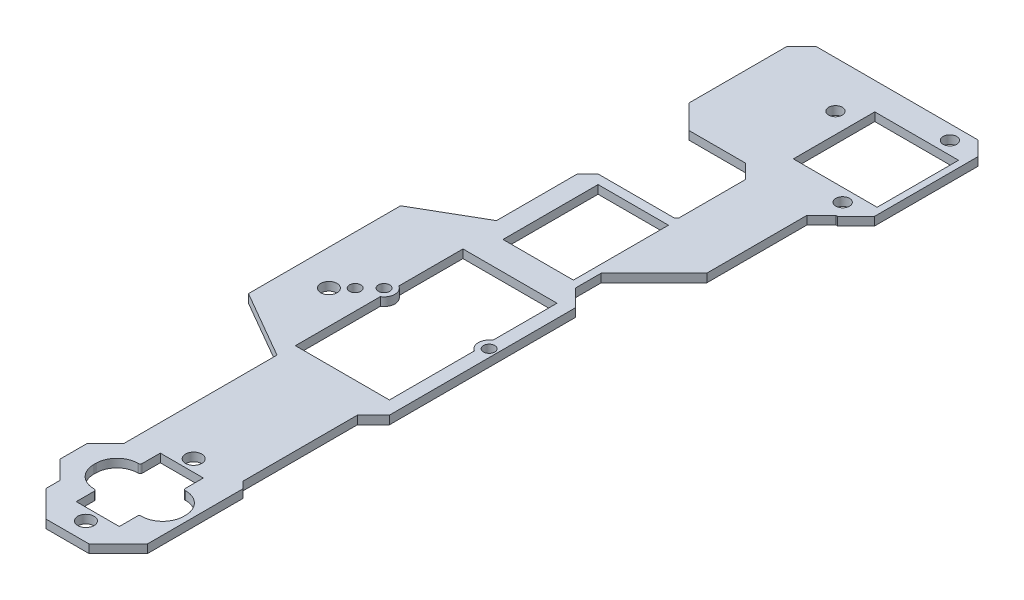
SolidWorks part; units mm, degrees
other "细节项目1" parameters "D6"=0, "D7"=43.265, "D8"=21.3195, "D9"=3.1, "D42"=2.165, "D1"=165.3052, "D2"=19.5925, "D3"=0.6425, "D4"=2.44, "D5"=17.2133, "D10"=7.7328, "D11"=1.0157, "D12"=7.6288, "D13"=2.2322, "D14"=28, "D15"=2.9581, "D16"=9.0669, "D17"=13.2064, "D18"=25.6687, "D19"=10.6252, "D20"=8.1415, "D21"=2.5001, "D22"=18.1, "D23"=31.9, "D24"=8.325, "D25"=16.4296, "D26"=39.8645, "D27"=14.2738, "D28"=3.5, "D29"=1.9207, "D30"=2.6491, "D31"=2.8766, "D32"=165.3052, "D33"=2.9084, "D34"=2.742, "D35"=4.9181, "D36"=3.9323, "D37"=15.95, "D38"=0.6899, "D39"=4.8396, "D40"=4.8539, "D41"=1.181, "D43"=5.1085, "D44"=5.1085, "D45"=13.8946, "D46"=1.2516
other "细节项目2"
other "DetailItem1" parameters "D1"=37.7393, "D2"=41.5714, "D3"=31.9, "D4"=17.9, "D5"=2.3612, "D6"=17.9
other "DetailItem2"
other "DetailItem3"
other "DetailItem4"
other "标注1"
sketch "草图2" plane through (-130.8299, 1.6, -83.1559) normal (0, 1, 0) x (1, 0, 0)
ref_plane "前视基准面" through (0, 0, 0) normal (0, 0, 1) x (1, 0, 0)
ref_plane "上视基准面" through (0, 0, 0) normal (0, 1, 0) x (1, 0, 0)
ref_plane "右视基准面" through (0, 0, 0) normal (1, 0, 0) x (0, 0, -1)
sketch "主结构参考-草图" plane through (0, 0, 0) normal (0, 1, 0) x (1, 0, 0)
  line L0 (0, 0) -> (0, -182.3314) construction
  line L1 (-33.5123, 83.1559) -> (-28.0234, 81.2061)
  line L2 (-19, -38) -> (-25.5, -38)
  line L3 (-25.5, -38) -> (-25.5, -41.5)
  line L4 (-25.5, -41.5) -> (-19, -41.5)
  line L5 (-19, -41.5) -> (-19, -38)
  line L6 (-35.683, -46.5466) -> (-25.6169, -51.6755)
  line L7 (-22.9814, -57.0983) -> (-24.5, -64.7956)
  line L8 (-24.5, -64.7956) -> (-24.5, -72.3717)
  line L9 (-24.5, -72.3717) -> (-22.5, -72.3717)
  line L10 (-22.5, -72.3717) -> (-22.5, -79.9478)
  line L11 (-22.5, -79.9478) -> (-24.1099, -79.9478)
  line L12 (-24.8532, -80.1135) -> (-37.6736, -86.1277)
  line L13 (-38.6804, -87.712) -> (-38.6804, -93.35)
  line L14 (-36.9304, -95.1) -> (-27.7511, -95.1)
  line L15 (-26.0011, -96.85) -> (-26.0011, -102.35)
  line L16 (-26.0011, -102.35) -> (-22.5, -102.35)
  line L17 (-22.5, -102.35) -> (-22.5, -110.35)
  line L18 (-22.5, -110.35) -> (-26.0011, -110.35)
  line L19 (-26.0011, -110.35) -> (-26.0011, -117.6)
  line L20 (-26.0011, -117.6) -> (-24.5011, -117.6)
  line L21 (-24.5011, -117.6) -> (-24.5011, -130.1)
  line L22 (-24.5011, -130.1) -> (-26.0011, -130.1)
  line L23 (0.0009, -58.5) -> (-4.1009, -58.5)
  line L25 (-4.1009, -58.5) -> (-4.1009, -61.9511)
  line L26 (-4.4509, -62.3011) -> (-4.5484, -62.3011)
  line L27 (-8.5484, -66.3011) -> (-8.5484, -66.6961)
  line L28 (-8.5484, -66.4986) -> (0, -66.4986) construction
  line L29 (-4.4509, -70.6961) -> (-4.5484, -70.6961)
  line L30 (-4.1009, -74.4972) -> (-4.1009, -71.0461)
  line L31 (0.0009, -74.4972) -> (-4.1009, -74.4972)
  line L32 (-0.0009, -58.5) -> (4.1009, -58.5)
  line L33 (4.1009, -58.5) -> (4.1009, -61.9511)
  line L34 (4.4509, -62.3011) -> (4.5484, -62.3011)
  line L35 (8.5484, -66.3011) -> (8.5484, -66.6961)
  line L36 (4.4509, -70.6961) -> (4.5484, -70.6961)
  line L37 (4.1009, -74.4972) -> (4.1009, -71.0461)
  line L38 (-0.0009, -74.4972) -> (4.1009, -74.4972)
  line L39 (25.5, -41.5) -> (19, -41.5)
  line L40 (25.5, -38) -> (25.5, -41.5)
  line L41 (19, -38) -> (25.5, -38)
  line L42 (19, -41.5) -> (19, -38)
  line L43 (24.5011, -130.1) -> (26.0011, -130.1)
  line L44 (24.5011, -117.6) -> (24.5011, -130.1)
  line L45 (26.0011, -117.6) -> (24.5011, -117.6)
  line L46 (26.0011, -110.35) -> (26.0011, -117.6)
  line L47 (22.5, -110.35) -> (26.0011, -110.35)
  line L48 (22.5, -102.35) -> (22.5, -110.35)
  line L49 (26.0011, -102.35) -> (22.5, -102.35)
  line L50 (26.0011, -96.85) -> (26.0011, -102.35)
  line L51 (36.9304, -95.1) -> (27.7511, -95.1)
  line L52 (38.6804, -87.712) -> (38.6804, -93.35)
  line L53 (24.8532, -80.1135) -> (37.6736, -86.1277)
  line L54 (22.5, -79.9478) -> (24.1099, -79.9478)
  line L55 (22.5, -72.3717) -> (22.5, -79.9478)
  line L56 (24.5, -72.3717) -> (22.5, -72.3717)
  line L57 (24.5, -64.7956) -> (24.5, -72.3717)
  line L58 (22.9814, -57.0983) -> (24.5, -64.7956)
  line L59 (35.683, -46.5466) -> (25.6169, -51.6755)
  line L60 (0, 0) -> (-130.8299, 0) construction
  line L61 (10.5, -81) -> (-10.5, -81)
  line L63 (-11.8487, -82.2911) -> (-13.5761, -121.8546)
  line L64 (-13.5761, -121.8546) -> (-13.5793, -125.7684)
  line L65 (-12.5918, -128.1539) -> (-7.25, -133.5)
  line L66 (-7.25, -133.5) -> (7.25, -133.5)
  line L68 (12.5918, -128.1539) -> (7.25, -133.5)
  line L69 (13.5761, -121.8546) -> (13.5793, -125.7684)
  line L70 (11.8487, -82.2911) -> (13.5761, -121.8546)
  line L85 (33.5123, 83.1559) -> (28.0234, 81.2061)
  line L99 (30.2498, 22.1218) -> (29.86, 20.4977)
  line L100 (31.0056, 27.0574) -> (30.2498, 22.1218)
  line L101 (27.1476, 31.0325) -> (20.9845, 30.1828)
  line L102 (29.86, -20.4977) -> (30.2498, -22.1218)
  line L103 (30.2498, -22.1218) -> (31.0056, -27.0574)
  line L104 (27.1476, -31.0325) -> (20.9845, -30.1828)
  line L105 (26.3691, 78.6288) -> (27.5605, 59.15)
  line L106 (-27.1476, -31.0325) -> (-20.9845, -30.1828)
  line L107 (-30.2498, -22.1218) -> (-31.0056, -27.0574)
  line L108 (-29.86, -20.4977) -> (-30.2498, -22.1218)
  line L109 (-30.2498, 22.1218) -> (-29.86, 20.4977)
  line L110 (-31.0056, 27.0574) -> (-30.2498, 22.1218)
  line L111 (-27.1476, 31.0325) -> (-20.9845, 30.1828)
  line L112 (25.5, 41.5) -> (19, 41.5)
  line L113 (19, 41.5) -> (19, 38)
  line L114 (19, 38) -> (25.5, 38)
  line L115 (25.5, 38) -> (25.5, 41.5)
  line L116 (5.75, 41.5) -> (-5.75, 41.5)
  line L117 (-5.75, 41.5) -> (-5.75, 38)
  line L118 (-5.75, 38) -> (5.75, 38)
  line L119 (5.75, 38) -> (5.75, 41.5)
  line L120 (23.6, 65.75) -> (7.65, 65.75)
  line L121 (7.65, 65.75) -> (7.65, 50.25)
  line L122 (7.65, 50.25) -> (23.6, 50.25)
  line L123 (23.6, 50.25) -> (23.6, 65.75)
  line L124 (-5.75, 38) -> (-5.75, 41.5)
  line L125 (5.75, 41.5) -> (5.75, 38)
  line L126 (-25.5, 38) -> (-25.5, 41.5)
  line L127 (-19, 38) -> (-25.5, 38)
  line L128 (-19, 41.5) -> (-19, 38)
  line L129 (-25.5, 41.5) -> (-19, 41.5)
  line L133 (27.8403, 57.7795) -> (29.754, 52.4001)
  line L134 (32.155, 49.6414) -> (40.1936, 45.4544)
  line L135 (-32.155, 49.6414) -> (-40.1936, 45.4544)
  line L136 (-27.8403, 57.7795) -> (-29.754, 52.4001)
  line L137 (-26.3691, 78.6288) -> (-27.5605, 59.15)
  arc A0 (-28.0234, 81.2061) -> (-26.3649, 78.6977) centre (-28.8602, 78.8503) cw
  arc A3 (28.0234, 81.2061) -> (26.3649, 78.6977) centre (28.8602, 78.8503) ccw
  circle A6 centre (-32, -42) radius 1.55
  circle A7 centre (-17.5, -47.5) radius 1.55
  arc A10 (-35.683, -46.5466) -> (-57.02, -48.2258) centre (-44.9813, -64.7956) ccw
  arc A12 (-22.9814, -57.0983) -> (-25.6169, -51.6755) centre (-27.8869, -56.1305) ccw
  arc A14 (-24.8532, -80.1135) -> (-24.1099, -79.9478) centre (-24.1099, -81.6978) cw
  arc A15 (-37.6736, -86.1277) -> (-38.6804, -87.712) centre (-36.9304, -87.712) ccw
  arc A16 (-38.6804, -93.35) -> (-36.9304, -95.1) centre (-36.9304, -93.35) ccw
  arc A17 (-27.7511, -95.1) -> (-26.0011, -96.85) centre (-27.7511, -96.85) cw
  circle A18 centre (0, -56.25) radius 1.55
  circle A19 centre (0, -76.75) radius 1.55
  circle A20 centre (-16.866, -65.108) radius 1.55
  arc A24 (-4.1009, -61.9511) -> (-4.4509, -62.3011) centre (-4.4509, -61.9511) cw
  arc A25 (-4.5484, -62.3011) -> (-8.5484, -66.3011) centre (-4.5484, -66.3011) ccw
  arc A26 (-4.5484, -70.6961) -> (-8.5484, -66.6961) centre (-4.5484, -66.6961) cw
  arc A27 (-4.1009, -71.0461) -> (-4.4509, -70.6961) centre (-4.4509, -71.0461) ccw
  arc A28 (4.1009, -61.9511) -> (4.4509, -62.3011) centre (4.4509, -61.9511) ccw
  arc A29 (4.5484, -62.3011) -> (8.5484, -66.3011) centre (4.5484, -66.3011) cw
  arc A30 (4.5484, -70.6961) -> (8.5484, -66.6961) centre (4.5484, -66.6961) ccw
  arc A31 (4.1009, -71.0461) -> (4.4509, -70.6961) centre (4.4509, -71.0461) cw
  circle A32 centre (32, -42) radius 1.55
  circle A33 centre (17.5, -47.5) radius 1.55
  arc A34 (27.7511, -95.1) -> (26.0011, -96.85) centre (27.7511, -96.85) ccw
  arc A35 (38.6804, -93.35) -> (36.9304, -95.1) centre (36.9304, -93.35) cw
  arc A36 (37.6736, -86.1277) -> (38.6804, -87.712) centre (36.9304, -87.712) cw
  arc A37 (24.8532, -80.1135) -> (24.1099, -79.9478) centre (24.1099, -81.6978) ccw
  arc A38 (22.9814, -57.0983) -> (25.6169, -51.6755) centre (27.8869, -56.1305) cw
  arc A39 (35.683, -46.5466) -> (57.02, -48.2258) centre (44.9813, -64.7956) cw
  circle A41 centre (16.866, -65.108) radius 1.55
  circle A42 centre (-34.5, -90.85) radius 1.55
  circle A43 centre (-16.9, -98.4) radius 1.55
  arc A44 (-10.5, -81) -> (-11.8487, -82.2911) centre (-10.5, -82.35) ccw
  arc A45 (-13.5793, -125.7684) -> (-12.5918, -128.1539) centre (-10.211, -125.7712) ccw
  circle A48 centre (-14.6, -133.5) radius 1.55
  circle A49 centre (-22.35, -133.5) radius 1.55
  arc A52 (13.5793, -125.7684) -> (12.5918, -128.1539) centre (10.211, -125.7712) cw
  arc A53 (10.5, -81) -> (11.8487, -82.2911) centre (10.5, -82.35) cw
  arc A63 (29.86, 20.4977) -> (29.86, -20.4977) centre (91.8849, 0) ccw
  arc A64 (31.0056, 27.0574) -> (27.1476, 31.0325) centre (28, 28) ccw
  arc A65 (20.9845, 30.1828) -> (18.059, 29.3089) centre (22.3504, 20.2765) ccw
  arc A66 (18.059, 29.3089) -> (-18.059, 29.3089) centre (0, 67.3193) cw
  arc A67 (31.0056, -27.0574) -> (27.1476, -31.0325) centre (28, -28) cw
  arc A68 (20.9845, -30.1828) -> (18.059, -29.3089) centre (22.3504, -20.2765) cw
  arc A69 (18.059, -29.3089) -> (-18.059, -29.3089) centre (0, -67.3193) ccw
  arc A70 (-20.9845, -30.1828) -> (-18.059, -29.3089) centre (-22.3504, -20.2765) ccw
  arc A71 (-31.0056, -27.0574) -> (-27.1476, -31.0325) centre (-28, -28) ccw
  arc A72 (-29.86, 20.4977) -> (-29.86, -20.4977) centre (-91.8849, 0) cw
  arc A73 (-31.0056, 27.0574) -> (-27.1476, 31.0325) centre (-28, 28) cw
  arc A74 (-20.9845, 30.1828) -> (-18.059, 29.3089) centre (-22.3504, 20.2765) cw
  circle A75 centre (36, 43) radius 1.55
  circle A76 centre (29.25, 40.5) radius 1.55
  circle A77 centre (19.5, 47.8) radius 1.3
  circle A78 centre (19.5, 68.2) radius 1.3
  circle A79 centre (3.8, 62.12) radius 1.3
  circle A80 centre (3.8, 74.15) radius 1.3
  circle A81 centre (-20.5, 74.15) radius 1.3
  circle A82 centre (-20.5, 62.12) radius 1.3
  circle A83 centre (-15, 53.5) radius 1.55
  circle A84 centre (-29.25, 40.5) radius 1.55
  circle A85 centre (-36, 43) radius 1.55
  arc A86 (27.5605, 59.15) -> (27.8403, 57.7795) centre (32.5512, 59.4553) ccw
  arc A87 (29.754, 52.4001) -> (32.155, 49.6414) centre (34.4648, 54.0759) ccw
  arc A88 (-29.754, 52.4001) -> (-32.155, 49.6414) centre (-34.4648, 54.0759) cw
  arc A89 (-27.5605, 59.15) -> (-27.8403, 57.7795) centre (-32.5512, 59.4553) cw
  point P249 (0, -133.5)
  point P250 (0, -81)
sketch "主结构参考2-草图" plane through (0, 0, 0) normal (0, 1, 0) x (1, 0, 0)
  line L0 (0, 0) -> (164.4446, 0) construction
  line L1 (56.8328, -48.3989) -> (84.4776, -68.4839)
  line L2 (0, -78.6558) -> (0, 78.6558) construction
  line L3 (-56.8328, -48.3989) -> (-84.4776, -68.4839)
  line L4 (0.25, -4.6996) -> (11.5388, -19.5881)
  line L5 (11.5388, -19.5881) -> (13.7761, -22.9243)
  line L6 (4.3699, 0) -> (22.5859, -13.8118)
  line L8 (4.3699, 0) -> (22.5859, 13.8118)
  line L9 (-11.5388, -19.5881) -> (-13.7761, -22.9243)
  line L10 (-0.25, -4.6996) -> (-11.5388, -19.5881)
  line L11 (56.8328, -48.3989) -> (84.4776, -68.4839)
  line L12 (-0.25, -29.9331) -> (0.25, -29.9331)
  line L13 (-56.8328, -48.3989) -> (-84.4776, -68.4839)
  line L15 (-4.3699, 0) -> (-22.5859, 13.8118)
  line L17 (-0.25, -4.6996) -> (0.25, -4.6996)
  line L18 (-0.25, -21.5644) -> (0.25, -21.5644)
  line L23 (30.5, 3.25) -> (30.5, -3.25)
  line L28 (34, 3.25) -> (30.5, 3.25)
  line L29 (-30.5, -3.25) -> (-34, -3.25)
  line L30 (-34, -3.25) -> (-34, 3.25)
  line L31 (-34, 3.25) -> (-30.5, 3.25)
  line L32 (-30.5, 3.25) -> (-30.5, -3.25)
  line L33 (-4.3699, 0) -> (-22.5859, -13.8118)
  line L34 (34, -3.25) -> (34, 3.25)
  line L35 (30.5, -3.25) -> (34, -3.25)
  line L36 (-0.25, 29.9331) -> (0.25, 29.9331)
  line L37 (-11.5388, 19.5881) -> (-13.7761, 22.9243)
  line L38 (-0.25, 4.6996) -> (-11.5388, 19.5881)
  line L39 (-0.25, 4.6996) -> (0.25, 4.6996)
  line L40 (0.25, 4.6996) -> (11.5388, 19.5881)
  line L41 (11.5388, 19.5881) -> (13.7761, 22.9243)
  line L42 (-0.25, 21.5644) -> (0.25, 21.5644)
  arc A0 (0.25, -29.9331) -> (56.8328, -48.3989) centre (0, -126.6225) cw
  circle A1 centre (-60.2246, -43.7557) radius 1.55
  arc A2 (-0.25, -29.9331) -> (-56.8328, -48.3989) centre (0, -126.6225) ccw
  arc A3 (0.25, -21.5644) -> (13.7761, -22.9243) centre (0, -91.9966) cw
  circle A4 centre (-44.0442, -32) radius 1.55
  circle A8 centre (-12.75, -12.75) radius 1.075
  circle A9 centre (-10, -10) radius 1.075
  circle A10 centre (-15.25, -15.25) radius 1.55
  arc A13 (-0.25, -21.5644) -> (-13.7761, -22.9243) centre (0, -91.9966) ccw
  arc A14 (0.25, -29.9331) -> (56.8328, -48.3989) centre (0, -126.6225) cw
  arc A15 (-0.25, -29.9331) -> (-56.8328, -48.3989) centre (0, -126.6225) ccw
  circle A16 centre (15.25, -15.25) radius 1.55
  circle A17 centre (10, -10) radius 1.075
  circle A18 centre (12.75, -12.75) radius 1.075
  circle A19 centre (44.0442, -32) radius 1.55
  circle A20 centre (60.2246, -43.7557) radius 1.55
  arc A24 (-28.8648, 17.1963) -> (-22.5859, 13.8118) centre (-41.8919, -14.4887) cw
  arc A25 (-28.8648, -17.1963) -> (-28.8648, 17.1963) centre (-91.8849, 0) ccw
  arc A26 (-22.5859, -13.8118) -> (-28.8648, -17.1963) centre (-41.8919, 14.4887) cw
  arc A27 (22.5859, -13.8118) -> (28.8648, -17.1963) centre (41.8919, 14.4887) ccw
  arc A28 (28.8648, -17.1963) -> (28.8648, 17.1963) centre (91.8849, 0) cw
  arc A29 (28.8648, 17.1963) -> (22.5859, 13.8118) centre (41.8919, -14.4887) ccw
  arc A30 (0.25, 29.9331) -> (56.8328, 48.3989) centre (0, 126.6225) ccw
  arc A31 (-0.25, 29.9331) -> (-56.8328, 48.3989) centre (0, 126.6225) cw
  arc A32 (-0.25, 21.5644) -> (-13.7761, 22.9243) centre (0, 91.9966) cw
  arc A33 (0.25, 21.5644) -> (13.7761, 22.9243) centre (0, 91.9966) ccw
  circle A34 centre (15.25, 15.25) radius 1.55
  circle A35 centre (12.75, 12.75) radius 1.075
  circle A36 centre (10, 10) radius 1.075
  circle A37 centre (-10, 10) radius 1.075
  circle A38 centre (-12.75, 12.75) radius 1.075
  circle A39 centre (-15.25, 15.25) radius 1.55
sketch "飞塔保护壳-参考-草图" plane through (0, 0, 0) normal (0, 1, 0) x (1, 0, 0)
  line L1 (-61.3007, 0) -> (77.257, 0) construction
  line L8 (-30.5, 3.25) -> (-34, 3.25)
  line L9 (-34, 3.25) -> (-34, -3.25)
  line L31 (-34, -3.25) -> (-30.5, -3.25)
  line L33 (-25.5, 38) -> (-25.5, 41.5)
  line L56 (-25.5, 41.5) -> (-19, 41.5)
  line L57 (-19, 41.5) -> (-19, 38)
  line L58 (-25.5, -38) -> (-25.5, -41.5)
  line L59 (-25.5, -41.5) -> (-19, -41.5)
  line L60 (-19, -41.5) -> (-19, -38)
  line L61 (19, -41.5) -> (19, -38)
  line L62 (25.5, -41.5) -> (19, -41.5)
  line L63 (25.5, -38) -> (25.5, -41.5)
  line L64 (19, 41.5) -> (19, 38)
  line L65 (25.5, 41.5) -> (19, 41.5)
  line L66 (25.5, 38) -> (25.5, 41.5)
  line L67 (34, -3.25) -> (30.5, -3.25)
  line L68 (34, 3.25) -> (34, -3.25)
  line L69 (30.5, 3.25) -> (34, 3.25)
  line L70 (-5.75, 38) -> (-5.75, 41.5)
  line L71 (-5.75, 41.5) -> (5.75, 41.5)
  line L72 (5.75, 41.5) -> (5.75, 38)
  line L73 (-5.75, 38) -> (-7.25, 36.5)
  line L75 (0, 68.5797) -> (0, -68.5797) construction
  line L78 (5.75, 38) -> (7.25, 36.5)
  line L83 (5.75, 38) -> (5.75, 32.8597)
  line L84 (19, 38) -> (19, 34.26)
  line L85 (-11.4662, -31.3366) -> (-10.3252, -32.103)
  line L86 (-10.3252, -32.103) -> (-10, -33.9347)
  line L87 (11.4662, -31.3366) -> (10.3252, -32.103)
  line L88 (10.3252, -32.103) -> (10, -33.9347)
  arc A49 (-25.5, 38) -> (-35.8347, 18.0724) centre (-25.2016, 25.2016) ccw
  arc A52 (-20.8758, 34.5817) -> (-34.0392, 19.854) centre (-25.2016, 25.2016) ccw
  arc A53 (-34.0392, -19.854) -> (-34.0392, 19.854) centre (-66.8509, 0) ccw
  arc A55 (-35.8347, -18.0724) -> (-30.5, -3.25) centre (-62.7894, 0) ccw
  arc A56 (-25.5, -38) -> (-35.8347, -18.0724) centre (-25.2016, -25.2016) cw
  arc A57 (-20.8758, -34.5817) -> (-34.0392, -19.854) centre (-25.2016, -25.2016) cw
  arc A59 (-30.5, 3.25) -> (-35.8347, 18.0724) centre (-62.7894, 0) ccw
  arc A62 (30.5, 3.25) -> (35.8347, 18.0724) centre (62.7894, 0) cw
  arc A65 (20.8758, -34.5817) -> (34.0392, -19.854) centre (25.2016, -25.2016) ccw
  arc A66 (25.5, -38) -> (35.8347, -18.0724) centre (25.2016, -25.2016) ccw
  arc A69 (35.8347, -18.0724) -> (30.5, -3.25) centre (62.7894, 0) cw
  arc A70 (34.0392, -19.854) -> (34.0392, 19.854) centre (66.8509, 0) cw
  arc A71 (20.8758, 34.5817) -> (34.0392, 19.854) centre (25.2016, 25.2016) cw
  arc A72 (25.5, 38) -> (35.8347, 18.0724) centre (25.2016, 25.2016) cw
  arc A73 (-19, 38) -> (19, 38) centre (0, 68.0682) ccw construction
  arc A74 (-20.8758, 34.5817) -> (20.8758, 34.5817) centre (0, 79.8492) ccw construction
  arc A75 (-19, -38) -> (19, -38) centre (0, -68.0682) cw
  arc A76 (-20.8758, -34.5817) -> (20.8758, -34.5817) centre (0, -79.8492) cw
  arc A80 (-20.8758, 34.5817) -> (20.8758, 34.5817) centre (0, 150.6569) ccw
  arc A81 (-7.25, 36.5) -> (-19, 38) centre (-11.5176, 49.8411) cw
  arc A82 (7.25, 36.5) -> (19, 38) centre (11.5176, 49.8411) ccw
  point P33 (-28.5, 0)
  point P34 (28.5, 0)
  point P37 (0, 30)
  point P38 (0, -30)
  point P54 (0, 32.5)
  point P60 (0, -32.5)
  dimension "D1" = 2
  dimension "D3" = 60
  dimension "D5" = 2.5
  dimension "D7" = 1.5
  dimension "D2" = 57
  dimension "D6" = 2.5
  dimension "D8" = 135
sketch "计算机底板参考-草图" plane through (0, 0, 0) normal (0, 1, 0) x (1, 0, 0)
  line L58 (-1000, -10.5223) -> (49000, -10.5223) construction
  line L59 (0, -10.5223) -> (0, 89.8504) construction
  line L60 (-41.25, -65.5223) -> (-34.3696, -65.5223)
  line L61 (41.25, -65.5223) -> (34.3696, -65.5223)
  line L62 (7.65, 71.8277) -> (23.6, 71.8277)
  line L63 (23.6, 71.8277) -> (23.6, 44.7277)
  line L64 (7.65, 50.25) -> (7.65, 71.8277)
  line L65 (35.75, 66.9777) -> (37.85, 66.9777)
  line L66 (37.85, 66.9777) -> (37.85, 58.4777)
  line L67 (37.85, 58.4777) -> (35.75, 58.4777)
  line L68 (35.75, 58.4777) -> (35.75, 66.9777)
  line L69 (35.75, 28.4777) -> (35.75, 36.9777)
  line L70 (35.75, 36.9777) -> (37.85, 36.9777)
  line L71 (37.85, 36.9777) -> (37.85, 28.4777)
  line L72 (37.85, 28.4777) -> (35.75, 28.4777)
  line L73 (35.75, -1.5223) -> (35.75, 6.9777) construction
  line L74 (35.75, 6.9777) -> (37.85, 6.9777) construction
  line L75 (37.85, 6.9777) -> (37.85, -1.5223) construction
  line L76 (37.85, -1.5223) -> (35.75, -1.5223) construction
  line L77 (35.75, -61.5223) -> (35.75, -53.0223)
  line L78 (35.75, -53.0223) -> (37.85, -53.0223)
  line L79 (37.85, -53.0223) -> (37.85, -61.5223)
  line L80 (-41.25, -65.5223) -> (-41.25, -10.5223)
  line L81 (7.65, 50.25) -> (15.4, 50.25)
  line L82 (37.85, -61.5223) -> (35.75, -61.5223)
  line L83 (15.4, 44.7277) -> (15.4, 50.25)
  line L84 (-37.85, -61.5223) -> (-37.85, -53.0223)
  line L85 (-37.85, -53.0223) -> (-35.75, -53.0223)
  line L86 (-41.25, -10.5223) -> (-41.25, 69.9777)
  line L87 (41.25, -65.5223) -> (41.25, -10.5223)
  line L88 (41.25, -10.5223) -> (41.25, 69.9777)
  line L89 (-41.25, 69.9777) -> (-36.6408, 77.961)
  line L90 (-36.6408, 77.961) -> (36.6408, 77.961)
  line L91 (41.25, 69.9777) -> (36.6408, 77.961)
  line L92 (35.75, -31.5223) -> (35.75, -23.0223)
  line L93 (35.75, -23.0223) -> (37.85, -23.0223)
  line L94 (37.85, -23.0223) -> (37.85, -31.5223)
  line L95 (37.85, -31.5223) -> (35.75, -31.5223)
  line L96 (35.75, 58.4777) -> (35.75, 28.4777) construction
  line L97 (-37.85, 58.4777) -> (-37.85, 66.9777)
  line L98 (-37.85, 66.9777) -> (-35.75, 66.9777)
  line L99 (-35.75, 66.9777) -> (-35.75, 58.4777)
  line L100 (-35.75, 58.4777) -> (-37.85, 58.4777)
  line L101 (-37.85, 28.4777) -> (-37.85, 36.9777)
  line L102 (-37.85, 36.9777) -> (-35.75, 36.9777)
  line L103 (-35.75, 36.9777) -> (-35.75, 28.4777)
  line L104 (-35.75, 28.4777) -> (-37.85, 28.4777)
  line L105 (-37.85, -1.5223) -> (-37.85, 6.9777) construction
  line L106 (-37.85, 6.9777) -> (-35.75, 6.9777) construction
  line L107 (-35.75, 6.9777) -> (-35.75, -1.5223) construction
  line L108 (-35.75, -1.5223) -> (-37.85, -1.5223) construction
  line L109 (-37.85, -31.5223) -> (-37.85, -23.0223)
  line L110 (-37.85, -23.0223) -> (-35.75, -23.0223)
  line L111 (-35.75, -23.0223) -> (-35.75, -31.5223)
  line L112 (-35.75, -31.5223) -> (-37.85, -31.5223)
  line L113 (15.4, 44.7277) -> (23.6, 44.7277)
  line L114 (-35.75, -53.0223) -> (-35.75, -61.5223)
  line L115 (-35.75, -61.5223) -> (-37.85, -61.5223)
  circle A19 centre (-15, 53.5) radius 1.55
  circle A20 centre (-17.5, -47.5) radius 1.55
  circle A21 centre (17.5, -47.5) radius 1.55
  arc A22 (-11.4407, -43.8407) -> (-34.3696, -65.5223) centre (-34.3696, -42.5576) cw
  arc A23 (-11.4407, -43.8407) -> (0, -33.0223) centre (0, -44.4809) cw
  arc A24 (11.4407, -43.8407) -> (34.3696, -65.5223) centre (34.3696, -42.5576) ccw
  arc A25 (11.4407, -43.8407) -> (0, -33.0223) centre (0, -44.4809) ccw
  circle A26 centre (32.325, 41.9777) radius 2.75 construction
  circle A27 centre (32.325, 41.9777) radius 1.55
  circle A28 centre (32.325, -45.5223) radius 1.55
  circle A29 centre (32.325, -45.5223) radius 2.75 construction
  circle A30 centre (-32.325, 41.9777) radius 1.55
  circle A31 centre (-32.325, -45.5223) radius 1.55
  circle A32 centre (-32.325, 41.9777) radius 2.75 construction
  circle A33 centre (-32.325, -45.5223) radius 2.75 construction
  circle A34 centre (-24.575, 28.4777) radius 1.55
  circle A35 centre (24.575, 28.4777) radius 1.55
  circle A36 centre (24.575, -29.5223) radius 1.55
  circle A37 centre (-24.575, -29.5223) radius 1.55
  point P117 (-41.25, -10.5223)
  point P120 (0, 44.4777)
  point P123 (41.25, -10.5223)
  point P169 (0, 77.961)
sketch "稳压模块接口参考-草图" plane through (0, 0, 0) normal (0, 1, 0) x (1, 0, 0)
  line L0 (-6.7, 27.4331) -> (6.7, 27.4331)
  line L1 (-8.95, 3.9669) -> (8.95, 3.9669)
  line L2 (-8.95, 3.9669) -> (-8.95, -27.9331)
  line L3 (-8.95, -27.9331) -> (8.95, -27.9331)
  line L4 (8.95, 3.9669) -> (8.95, -27.9331)
  line L5 (-6.7, 27.4331) -> (-6.7, 9.3331)
  line L6 (-6.7, 9.3331) -> (6.7, 9.3331)
  line L7 (6.7, 27.4331) -> (6.7, 9.3331)
  line L8 (0, 0) -> (0, -39.2731) construction
  line L9 (0, 0) -> (0, -182.3314) construction
sketch "主结构-草图" plane through (0, 0, 0) normal (0, 1, 0) x (1, 0, 0)
  line L0 (0, 0) -> (0, 165.3052) construction
  line L1 (0, 0) -> (227.5923, 0) construction
  line L2 (6.5, 42.25) -> (6.5, 28.6515) construction
  line L3 (6.5, 42.25) -> (3.75, 45)
  line L4 (3.75, 45) -> (-11.5, 45) construction
  line L5 (-11.5, 45) -> (-11.5, 70.95) construction
  line L6 (-11.5, 70.95) -> (22.1, 70.95) construction
  line L7 (22.1, 70.95) -> (24.85, 68.2)
  line L8 (24.85, 68.2) -> (24.85, 48.5)
  line L9 (24.85, 48.5) -> (21.35, 45)
  line L10 (21.35, 45) -> (21, 45)
  line L11 (21, 45) -> (18.25, 42.25)
  line L12 (18.25, 42.25) -> (18.25, 30.1707)
  line L13 (19, 41.5) -> (19, 38) construction
  line L14 (5.75, 38) -> (5.75, 41.5) construction
  line L15 (23.6, 50.25) -> (23.6, 65.75) construction
  line L16 (-3.2705, 51.3409) -> (3.2705, 51.3409) construction
  line L17 (25.5, 41.5) -> (19, 41.5) construction
  line L18 (-3.2705, 53.0124) -> (3.2705, 53.0124) construction
  line L19 (-3.2705, 49.6693) -> (3.2705, 49.6693) construction
  line L20 (-3.2705, 66.385) -> (3.2705, 66.385) construction
  line L21 (-3.2705, 68.0566) -> (3.2705, 68.0566) construction
  line L22 (-3.2705, 64.7135) -> (3.2705, 64.7135) construction
  line L23 (0, -78.6558) -> (0, 78.6558) construction
  line L24 (7.65, 65.75) -> (23.6, 65.75)
  line L25 (23.6, 65.75) -> (23.6, 50.25)
  line L26 (23.6, 50.25) -> (7.65, 50.25)
  line L27 (7.65, 50.25) -> (7.65, 65.75)
  line L28 (18.25, 31.6707) -> (44.1545, 31.6707) construction
  line L29 (6.5, 30.1515) -> (11.8841, 30.1515) construction
  line L30 (-20.8758, 34.5817) -> (-20.8758, 30.7132) construction
  line L33 (-20.8758, 32.2132) -> (-28.5046, 32.2132) construction
  line L34 (-32.5392, 19.854) -> (-34.0392, 19.854) construction
  line L35 (-32.5392, -19.854) -> (-34.0392, -19.854) construction
  line L36 (28.36, -20.4977) -> (29.86, -20.4977) construction
  line L38 (-9.65, -32.6688) -> (9.65, -32.6688) construction
  line L48 (6.5, 42.25) -> (6.5, 29.6831)
  line L49 (-22.9204, 2.2303) -> (-22.9204, -2.2303) construction
  line L50 (-20.2382, 2.2303) -> (-20.2382, -2.2303) construction
  line L51 (-25.6027, 2.2303) -> (-25.6027, -2.2303) construction
  line L52 (-9.65, -29.2171) -> (-9.65, -32.6688) construction
  line L57 (6.5, 29.6831) -> (6, 29.1831)
  line L58 (9.65, -29.2171) -> (9.65, -32.6688) construction
  line L59 (6, 29.1831) -> (-10.425, 29.1831) construction
  line L60 (-10.425, 29.1831) -> (-10.425, 11.8242) construction
  line L61 (-10.425, 11.8242) -> (-22, 5.1414)
  line L62 (-22, 5.1414) -> (-22, -23.8127)
  line L63 (-22, -23.8127) -> (-9.65, -30.943)
  line L64 (-9.65, -30.943) -> (-9.65, -80.25) construction
  line L65 (-9.65, -80.25) -> (9.65, -80.25) construction
  line L66 (9.65, -80.25) -> (9.65, -29.2171) construction
  line L68 (11.45, -30.4561) -> (11.45, 5.0145)
  line L69 (11.45, 5.0145) -> (8.2, 8.2645)
  line L70 (8.2, 8.2645) -> (8.2, 13.1275)
  line L72 (6, 29.1831) -> (-8.425, 29.1831)
  line L73 (-8.425, 29.1831) -> (-10.425, 27.1831)
  line L74 (-10.425, 27.1831) -> (-10.425, 11.8242)
  line L75 (22.1, 70.95) -> (-8.75, 70.95)
  line L76 (-8.75, 70.95) -> (-11.5, 68.2)
  line L77 (-11.5, 68.2) -> (-11.5, 49.5)
  line L78 (-11.5, 49.5) -> (-7, 45)
  line L79 (-7, 45) -> (3.75, 45)
  line L80 (-11.675, 12.75) -> (-11.675, 14.5743) construction
  line L83 (18.25, 30.1707) -> (18.25, 23.1775)
  line L84 (18.25, 23.1775) -> (8.2, 13.1275)
  line L85 (6.7, 27.4331) -> (6.7, 9.3331) construction
  line L86 (8.95, 3.9669) -> (8.95, -27.9331) construction
  line L88 (-9.15, -34.1228) -> (-9.15, -75.2009) construction
  line L90 (-9.15, -75.2009) -> (-4.1009, -80.25)
  line L91 (-4.1009, -80.25) -> (4.1009, -80.25)
  line L92 (4.1009, -80.25) -> (9.65, -74.7009)
  line L93 (9.65, -74.7009) -> (9.65, -56.5)
  line L94 (9.65, -56.5) -> (8.4, -55.25)
  line L95 (8.4, -55.25) -> (8.4, -33.5061)
  line L96 (8.4, -33.5061) -> (11.45, -30.4561)
  line L97 (-0.0009, -58.5) -> (4.1009, -58.5) construction
  line L98 (-4.1009, -74.4972) -> (-4.1009, -71.0461) construction
  line L99 (4.1009, -74.4972) -> (4.1009, -71.0461) construction
  line L100 (0, 0) -> (-130.8299, 0) construction
  line L101 (5.75, 41.5) -> (-5.75, 41.5) construction
  line L102 (-4.1009, -58.5) -> (-4.1009, -61.9511)
  line L103 (-9.15, -34.1228) -> (-9.15, -60.4511)
  line L104 (-9.15, -60.4511) -> (-12.65, -63.9511)
  line L105 (-12.65, -63.9511) -> (-12.65, -69.0461)
  line L106 (-12.65, -69.0461) -> (-9.15, -72.5461)
  line L107 (-9.15, -72.5461) -> (-9.15, -75.2009)
  line L108 (-4.5484, -62.3011) -> (-4.4509, -62.3011)
  line L109 (-4.5484, -70.6961) -> (-4.4509, -70.6961)
  line L110 (-4.1009, -71.0461) -> (-4.1009, -74.4972)
  line L111 (-4.1009, -74.4972) -> (0.0009, -74.4972)
  line L112 (-8.5484, -66.3011) -> (-8.5484, -66.6961)
  line L113 (0.0009, -58.5) -> (-4.1009, -58.5)
  line L114 (4.1009, -74.4972) -> (-0.0009, -74.4972)
  line L115 (4.1009, -71.0461) -> (4.1009, -74.4972)
  line L116 (4.5484, -70.6961) -> (4.4509, -70.6961)
  line L117 (8.5484, -66.3011) -> (8.5484, -66.6961)
  line L118 (4.5484, -62.3011) -> (4.4509, -62.3011)
  line L119 (4.1009, -58.5) -> (4.1009, -61.9511)
  line L120 (-0.0009, -58.5) -> (4.1009, -58.5)
  line L121 (-8.95, 3.9669) -> (8.95, 3.9669)
  line L122 (8.95, 3.9669) -> (8.95, -27.9331) construction
  line L123 (8.95, -27.9331) -> (-8.95, -27.9331)
  line L124 (-8.95, -27.9331) -> (-8.95, 3.9669) construction
  line L125 (-6.7, 27.4331) -> (6.7, 27.4331)
  line L126 (6.7, 27.4331) -> (6.7, 9.3331)
  line L127 (6.7, 9.3331) -> (-6.7, 9.3331)
  line L128 (-6.7, 9.3331) -> (-6.7, 27.4331)
  line L129 (-8.95, 3.9669) -> (-8.95, -27.9331) construction
  line L130 (-8.95, 3.9669) -> (-8.95, -8.2393)
  line L131 (-8.95, -11.7607) -> (-8.95, -27.9331)
  line L132 (8.95, -11.7607) -> (8.95, -27.9331)
  line L133 (8.95, 3.9669) -> (8.95, -8.2393)
  line L135 (-10.5131, 63.8885) -> (-5.4331, 63.8885) construction
  line L136 (-10.5131, 63.8885) -> (-10.5131, 54.5485) construction
  line L137 (-10.5131, 54.5485) -> (-5.4331, 54.5485) construction
  line L138 (-5.4331, 63.8885) -> (-5.4331, 54.5485) construction
  line L139 (-9.65, -30.943) -> (-9.15, -31.2316)
  line L140 (-9.15, -31.2316) -> (-9.15, -34.1228)
  circle A0 centre (19.5, 68.2) radius 1.3
  circle A1 centre (19.5, 68.2) radius 1.3 construction
  arc A2 (-3.2705, 53.0124) -> (-3.2705, 49.6693) centre (-3.2705, 51.3409) ccw construction
  arc A3 (3.2705, 49.6693) -> (3.2705, 53.0124) centre (3.2705, 51.3409) ccw construction
  arc A4 (-3.2705, 68.0566) -> (-3.2705, 64.7135) centre (-3.2705, 66.385) ccw construction
  arc A5 (3.2705, 64.7135) -> (3.2705, 68.0566) centre (3.2705, 66.385) ccw construction
  circle A6 centre (19.5, 47.8) radius 1.3
  circle A7 centre (19.5, 47.8) radius 1.3 construction
  arc A9 (-20.8758, 30.7132) -> (18.25, 30.1707) centre (0.2997, 146.7342) ccw construction
  arc A11 (-20.8758, 34.5817) -> (20.8758, 34.5817) centre (0, 150.6569) ccw construction
  arc A13 (-56.8328, 48.3989) -> (-0.25, 29.9331) centre (0, 126.6225) ccw construction
  arc A18 (0.25, 29.9331) -> (56.8328, 48.3989) centre (0, 126.6225) ccw construction
  arc A24 (-20.8758, 30.7132) -> (-32.5392, 19.854) centre (-22.6602, 20.9366) ccw construction
  circle A25 centre (-15.25, -15.25) radius 1.55
  circle A26 centre (-12.75, -12.75) radius 1.075
  circle A27 centre (-10, -10) radius 1.075
  circle A31 centre (-15.25, -15.25) radius 1.55 construction
  circle A32 centre (-12.75, -12.75) radius 1.075 construction
  circle A33 centre (-10, -10) radius 1.075 construction
  circle A34 centre (-10, 10) radius 1.075 construction
  circle A35 centre (-12.75, 12.75) radius 1.075
  circle A36 centre (-15.25, 15.25) radius 1.55
  circle A37 centre (15.25, 15.25) radius 1.55
  circle A38 centre (12.75, 12.75) radius 1.075
  circle A39 centre (10, 10) radius 1.075
  circle A40 centre (10, -10) radius 1.075
  circle A41 centre (12.75, -12.75) radius 1.075
  circle A42 centre (15.25, -15.25) radius 1.55
  arc A43 (-20.2382, 2.2303) -> (-25.6027, 2.2303) centre (-22.9204, 2.2303) ccw construction
  arc A44 (-25.6027, -2.2303) -> (-20.2382, -2.2303) centre (-22.9204, -2.2303) ccw construction
  arc A45 (-32.5392, 19.854) -> (-32.5392, -19.854) centre (-65.3509, 0) cw construction
  arc A46 (-34.0392, -19.854) -> (-34.0392, 19.854) centre (-66.8509, 0) ccw construction
  arc A47 (-20.8758, -30.7132) -> (-32.5392, -19.854) centre (-22.6602, -20.9366) cw construction
  arc A48 (-20.8758, -30.7132) -> (18.25, -30.1707) centre (0.2997, -146.7342) cw construction
  arc A49 (20.8758, -30.7132) -> (32.5392, -19.854) centre (22.6602, -20.9366) ccw construction
  arc A50 (32.5392, 19.854) -> (32.5392, -19.854) centre (65.3509, 0) ccw construction
  arc A51 (20.8758, 30.7132) -> (32.5392, 19.854) centre (22.6602, 20.9366) cw construction
  arc A52 (20.8758, 30.7132) -> (18.25, 30.1707) centre (-4.2997, 145.9324) cw construction
  arc A53 (20.8758, -30.7132) -> (18.25, -30.1707) centre (-4.2997, -145.9324) ccw construction
  arc A54 (-9.65, -29.2171) -> (-20.8758, -30.7132) centre (0.2997, -146.7342) ccw construction
  arc A55 (18.25, -30.1707) -> (9.65, -29.2171) centre (2.7019, -131.1348) ccw construction
  arc A56 (19, -38) -> (-19, -38) centre (0, -68.0682) ccw construction
  arc A57 (20.8758, -34.5817) -> (-20.8758, -34.5817) centre (0, -79.8492) ccw construction
  circle A58 centre (3.8, 62.12) radius 1.3
  circle A59 centre (3.8, 62.12) radius 1.3 construction
  circle A60 centre (0, -56.25) radius 1.55
  circle A61 centre (0, -76.75) radius 1.55
  circle A62 centre (0, -56.25) radius 1.55 construction
  arc A63 (-4.5484, -62.3011) -> (-8.5484, -66.3011) centre (-4.5484, -66.3011) ccw
  arc A64 (-4.1009, -61.9511) -> (-4.4509, -62.3011) centre (-4.4509, -61.9511) cw
  arc A65 (-4.4509, -70.6961) -> (-4.1009, -71.0461) centre (-4.4509, -71.0461) cw
  arc A66 (-4.5484, -62.3011) -> (-8.5484, -66.3011) centre (-4.5484, -66.3011) ccw construction
  arc A67 (-8.5484, -66.6961) -> (-4.5484, -70.6961) centre (-4.5484, -66.6961) ccw construction
  arc A68 (-8.5484, -66.6961) -> (-4.5484, -70.6961) centre (-4.5484, -66.6961) ccw
  arc A69 (-4.1009, -71.0461) -> (-4.4509, -70.6961) centre (-4.4509, -71.0461) ccw construction
  arc A70 (4.4509, -70.6961) -> (4.1009, -71.0461) centre (4.4509, -71.0461) ccw
  arc A71 (8.5484, -66.6961) -> (4.5484, -70.6961) centre (4.5484, -66.6961) cw
  arc A72 (4.5484, -62.3011) -> (8.5484, -66.3011) centre (4.5484, -66.3011) cw
  arc A73 (4.1009, -61.9511) -> (4.4509, -62.3011) centre (4.4509, -61.9511) ccw
  arc A74 (-8.95, -8.2393) -> (-8.95, -11.7607) centre (-10, -10) cw
  arc A75 (8.95, -8.2393) -> (8.95, -11.7607) centre (10, -10) ccw
  point P31 (0, 51.3409)
  point P39 (0, 66.385)
  point P136 (-11.675, 13.6622)
  point P161 (-22.9204, 0)
extrude "主结构-PCB最大范围-实际可以比这个小" add sketch "主结构-草图" along normal blind 1.6
